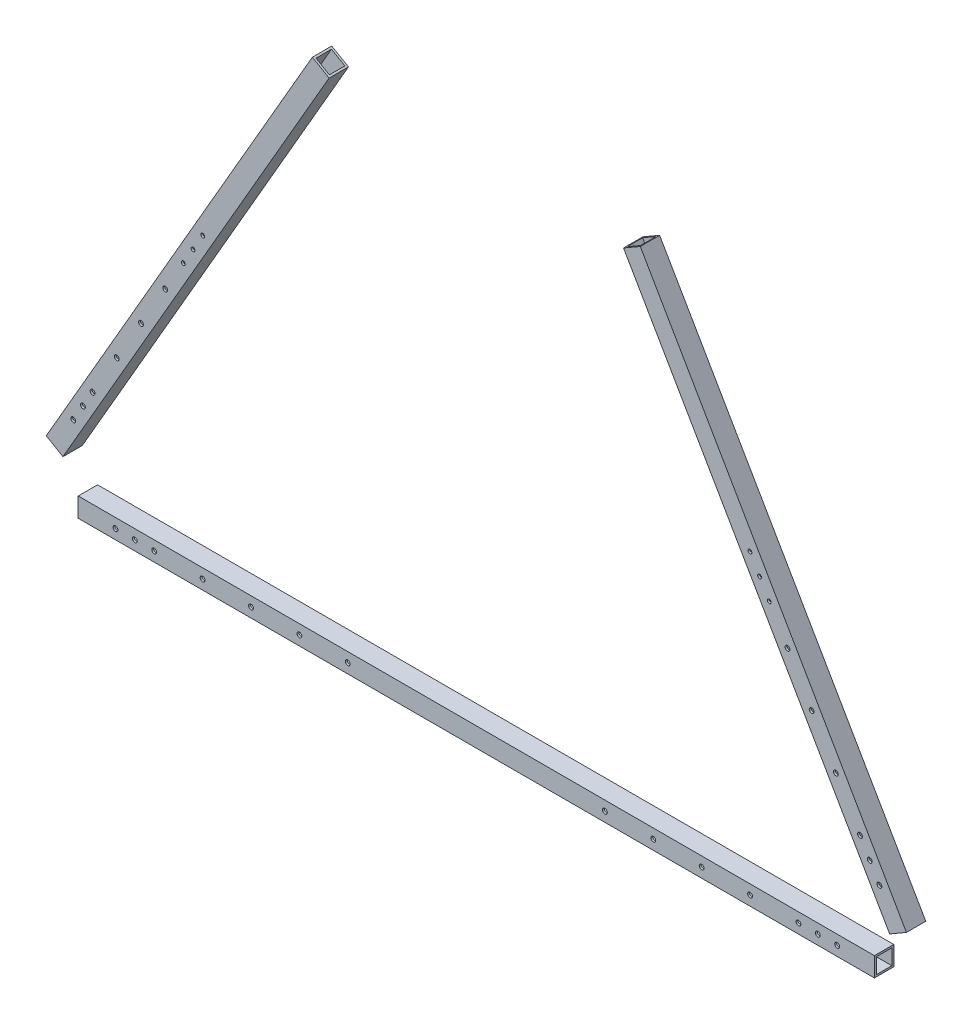
SolidWorks part; units mm, degrees
ref_plane "前视基准面" through (0, 0, 0) normal (0, 0, 1) x (1, 0, 0)
ref_plane "上视基准面" through (0, 0, 0) normal (0, 1, 0) x (1, 0, 0)
ref_plane "右视基准面" through (0, 0, 0) normal (1, 0, 0) x (0, 0, -1)
sketch "草图2" plane through (0, 0, 0) normal (0, 0, 1) x (1, 0, 0)
  line L0 (0, 0) -> (150, 0) construction
  line L1 (150, 0) -> (438.6751, -500)
  line L3 (0, -1000) -> (0, 49000) construction
  line L4 (-150, 0) -> (-438.6751, -500)
  line L5 (438.6751, -500) -> (-438.6751, -500)
  line L6 (150, 0) -> (52.8422, -56.0941) construction
  dimension "D1" = 150
  dimension "D2" = 500
  dimension "D3" = 60
  dimension "D5" = 112.1882
ref_plane "基准面4" through (37.5, -64.9519, 0) normal (-0.5, 0.866, 0) x (-0.866, -0.5, 0)
sketch "草图3" plane through (37.5, -64.9519, 0) normal (-0.5, 0.866, 0) x (-0.866, -0.5, 0)
  line L1 (-150.3025, 8) -> (-134.3025, 8)
  line L2 (-150.3025, 8) -> (-150.3025, -8)
  line L3 (-150.3025, -8) -> (-134.3025, -8)
  line L4 (-134.3025, 8) -> (-134.3025, -8)
  line L5 (-150.3025, 8) -> (-134.3025, -8) construction
  line L6 (-150.3025, -8) -> (-134.3025, 8) construction
  line L7 (-129.9038, 0) -> (-17.7156, 0) construction
  line L9 (-152.3025, 10) -> (-132.3025, 10)
  line L10 (-152.3025, 10) -> (-152.3025, -10)
  line L11 (-152.3025, -10) -> (-132.3025, -10)
  line L12 (-132.3025, 10) -> (-132.3025, -10)
  line L13 (-152.3025, 10) -> (-132.3025, -10) construction
  line L14 (-152.3025, -10) -> (-132.3025, 10) construction
  point P0 (-142.3025, 0)
  point P9 (-142.3025, 0)
  dimension "D1" = 16
  dimension "D2" = 20
  dimension "D3" = 20
sweep "扫描1" add profiles "草图3" path "草图2"
sketch "草图4" plane through (0, 0, 10) normal (0, 0, 1) x (1, 0, 0)
  line L0 (0, 169.5605) -> (0, -791.822) construction
  line L1 (0, -11) -> (0, 11) construction
  line L2 (-477.4708, -522.3987) -> (101.7631, -187.9778) construction
  line L3 (-477.4708, -522.3987) -> (-442.8298, -502.3987) construction
  line L4 (477.4708, -522.3987) -> (-40.9486, -223.0891) construction
  line L5 (477.4708, -522.3987) -> (442.8298, -502.3987) construction
  line L6 (-444.3978, -465.1146) -> (-427.0773, -475.1146)
  line L7 (-169.3978, 11.1993) -> (-477.4708, -522.3987) construction
  line L8 (-152.0773, 1.1993) -> (-442.8298, -502.3987) construction
  line L9 (-152.0773, 1.1993) -> (-169.3978, 11.1993) construction
  line L10 (-411.3249, -522.3987) -> (-411.3249, -502.3987)
  line L11 (-444.3978, -465.1146) -> (-477.4708, -522.3987)
  line L12 (-477.4708, -522.3987) -> (-411.3249, -522.3987)
  line L13 (-411.3249, -502.3987) -> (-442.8298, -502.3987)
  line L14 (-442.8298, -502.3987) -> (-427.0773, -475.1146)
  line L15 (411.3249, -502.3987) -> (442.8298, -502.3987)
  line L16 (411.3249, -522.3987) -> (411.3249, -502.3987)
  line L17 (477.4708, -522.3987) -> (411.3249, -522.3987)
  line L18 (444.3978, -465.1146) -> (477.4708, -522.3987)
  line L19 (444.3978, -465.1146) -> (427.0773, -475.1146)
  line L20 (442.8298, -502.3987) -> (427.0773, -475.1146)
  circle A0 centre (-302.7187, -239.7192) radius 2 construction
  circle A1 centre (-292.7187, -222.3987) radius 2 construction
  circle A2 centre (-282.7187, -205.0782) radius 2 construction
  circle A3 centre (-302.7187, -239.7192) radius 2
  circle A4 centre (-292.7187, -222.3987) radius 2
  circle A5 centre (-282.7187, -205.0782) radius 2
  circle A6 centre (282.7187, -205.0782) radius 2
  circle A7 centre (292.7187, -222.3987) radius 2
  circle A8 centre (302.7187, -239.7192) radius 2
  dimension "D1" = 550
extrude "切除-拉伸1" cut sketch "草图4" against normal through all
sketch "草图5" plane through (0, 0, 10) normal (0, 0, 1) x (1, 0, 0)
  line L0 (-443.6875, -512.3987) -> (507.711, -512.3987) construction
  line L1 (-411.3249, -522.3987) -> (411.3249, -522.3987) construction
  line L2 (-411.3249, -522.3987) -> (-411.3249, -502.3987) construction
  line L3 (0, 234.6252) -> (0, -913.3368) construction
  line L4 (-332.8249, -512.3987) -> (-282.8249, -512.3987) construction
  line L5 (-477.4708, -522.3987) -> (64.6759, -209.3901) construction
  line L6 (-411.3249, -522.3987) -> (-477.4708, -522.3987) construction
  line L7 (-444.3978, -465.1146) -> (-477.4708, -522.3987) construction
  line L8 (-169.3978, 11.1993) -> (-444.3978, -465.1146) construction
  circle A0 centre (-372.8249, -512.3987) radius 2.5
  circle A1 centre (-352.8249, -512.3987) radius 2.5
  circle A2 centre (-332.8249, -512.3987) radius 2.5
  circle A3 centre (-282.8249, -512.3987) radius 2.5
  circle A4 centre (-232.8249, -512.3987) radius 2.5
  circle A5 centre (-182.8249, -512.3987) radius 2.5
  circle A6 centre (-132.8249, -512.3987) radius 2.5
  circle A8 centre (-321.4876, -272.2278) radius 2.5
  circle A9 centre (-346.4876, -315.5291) radius 2.5
  circle A10 centre (-371.4876, -358.8304) radius 2.5
  circle A11 centre (-396.4876, -402.1316) radius 2.5
  circle A12 centre (-406.4876, -419.4521) radius 2.5
  circle A13 centre (-416.4876, -436.7727) radius 2.5
  circle A14 centre (232.8249, -512.3987) radius 2.5
  circle A15 centre (282.8249, -512.3987) radius 2.5
  circle A16 centre (332.8249, -512.3987) radius 2.5
  circle A17 centre (352.8249, -512.3987) radius 2.5
  circle A18 centre (372.8249, -512.3987) radius 2.5
  circle A19 centre (132.8249, -512.3987) radius 2.5
  circle A20 centre (182.8249, -512.3987) radius 2.5
  circle A21 centre (396.4876, -402.1316) radius 2.5
  circle A22 centre (371.4876, -358.8304) radius 2.5
  circle A23 centre (346.4876, -315.5291) radius 2.5
  circle A24 centre (321.4876, -272.2278) radius 2.5
  circle A25 centre (416.4876, -436.7727) radius 2.5
  circle A26 centre (406.4876, -419.4521) radius 2.5
  dimension "D2" = 5
  dimension "D3" = 38.5
  dimension "D5" = 20
  dimension "D1" = 10
  dimension "D4" = 3
  dimension "D7" = 50
  dimension "D8" = 30
  dimension "D6" = 5
extrude "切除-拉伸2" cut sketch "草图5" against normal through all
